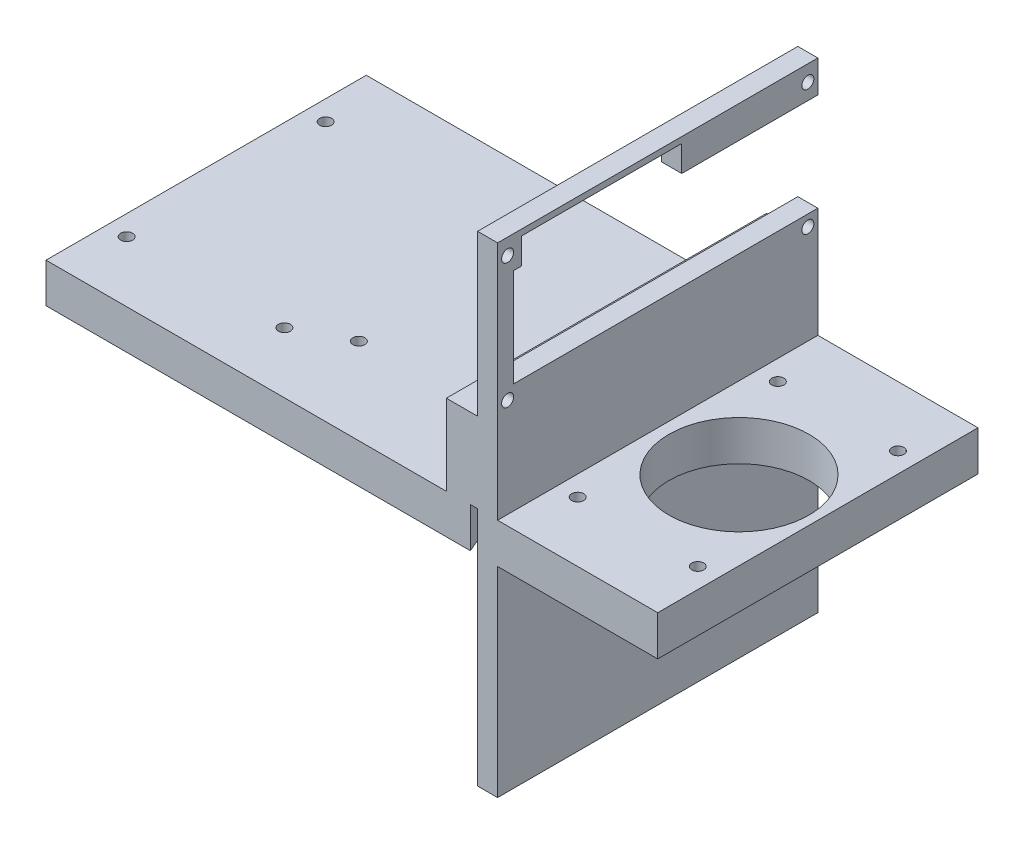
SolidWorks part; units mm, degrees
ref_plane "Front Plane" through (0, 0, 0) normal (0, 0, 1) x (1, 0, 0)
ref_plane "Top Plane" through (0, 0, 0) normal (0, 1, 0) x (1, 0, 0)
ref_plane "Right Plane" through (0, 0, 0) normal (1, 0, 0) x (0, 0, -1)
sketch "Sketch1" plane through (0, 0, 0) normal (0, 0, 1) x (1, 0, 0)
  line L0 (0, 0) -> (0, 30)
  line L1 (0, 30) -> (12.8, 30)
  line L2 (12.8, 30) -> (12.8, 0)
  line L3 (12.8, 0) -> (7.8, 0)
  line L4 (7.8, 0) -> (7.8, 10)
  line L5 (7.8, 10) -> (6, 10)
  line L6 (6, 10) -> (6, 0)
  line L7 (6, 0) -> (0, 0)
  dimension "D1" = 1.8
  dimension "D2" = 6
  dimension "D3" = 5
  dimension "D4" = 30
  dimension "D5" = 10
extrude "Boss-Extrude1" add sketch "Sketch1" along normal blind 80
sketch "Sketch3" plane through (0, 0, 0) normal (0, -1, 0) x (1, 0, 0)
  line L0 (7.8, 80) -> (12.8, 80)
  line L1 (12.8, 80) -> (12.8, 0)
  line L2 (12.8, 0) -> (7.8, 0)
  line L3 (7.8, 0) -> (7.8, 80)
sketch "Esboço2" plane through (0, 0, 0) normal (0, -1, 0) x (1, 0, 0)
  line L0 (6, 80) -> (6, 0)
  arc A0 (6, 80) -> (6, 0) centre (93.9293, 40) ccw
  dimension "D1" = 96.6
extrude "Corte-extrusão1" cut sketch "Esboço2" against normal blind 10
extrude "Boss-Extrude2" add sketch "Sketch3" along normal blind 50
sketch "Sketch4" plane through (0, 0, 0) normal (-1, 0, 0) x (0, 0, 1)
  line L0 (80, 30) -> (80, 0) construction
  line L1 (80, 9.8625) -> (0, 9.8625)
  line L2 (80, 9.8625) -> (80, 0)
  line L3 (80, 0) -> (0, 0)
  line L4 (0, 9.8625) -> (0, 0)
extrude "Boss-Extrude3" add sketch "Sketch4" along normal blind 100
sketch "Sketch5" plane through (0, 9.8625, 0) normal (0, 1, 0) x (1, 0, 0)
  line L0 (-100, -80) -> (0, -80) construction
  line L2 (-100, 0) -> (0, 0) construction
  line L3 (-100, -80) -> (-100, 0) construction
  circle A5 centre (-6.5, -21.55) radius 1.5
  circle A6 centre (-6.5, -58.45) radius 1.5
  circle A7 centre (-43.4, -21.55) radius 1.5
  circle A8 centre (-43.4, -58.45) radius 1.5
  circle A9 centre (-55.6, -64.85) radius 1.5
  circle A10 centre (-95, -64.85) radius 1.5
  circle A11 centre (-95, -15.15) radius 1.5
  point P26 (0, 0)
  point P31 (0, 0)
  point P32 (0, 0)
  dimension "D9" = 3
  dimension "D14" = 3
  dimension "D2" = 12.2
  dimension "D10" = 36.9
  dimension "D11" = 36.9
  dimension "D12" = 21.55
  dimension "D15" = 39.4
  dimension "D16" = 49.7
  dimension "D17" = 5
  dimension "D18" = 15.15
extrude "Cut-Extrude1" cut sketch "Sketch5" against normal blind 40
sketch "Sketch6" plane through (0, 30, 0) normal (0, 1, 0) x (1, 0, 0)
  line L0 (12.8, -80) -> (0, -80) construction
  line L1 (12.8, 0) -> (7.8, 0)
  line L2 (12.8, 0) -> (12.8, -80)
  line L3 (12.8, -80) -> (7.8, -80)
  line L4 (7.8, 0) -> (7.8, -80)
  dimension "D1" = 5
extrude "Boss-Extrude4" add sketch "Sketch6" along normal blind 40
sketch "Sketch7" plane through (12.8, 0, 0) normal (1, 0, 0) x (0, 0, -1)
  line L0 (-74, 68.5) -> (-74, 62)
  line L1 (-74, 62) -> (-76, 62)
  line L2 (-76, 62) -> (-76, 37.5)
  line L3 (-76, 37.5) -> (0, 37.5)
  line L4 (0, 37.5) -> (0, 62)
  line L5 (0, 62) -> (-34, 62)
  line L6 (-34, 62) -> (-34, 68.5)
  line L7 (-34, 68.5) -> (-74, 68.5)
  line L8 (-80, -50) -> (-80, 70) construction
  line L9 (-80, 70) -> (0, 70) construction
  line L10 (-85.9777, 68.5) -> (4.9186, 68.5) construction
  line L11 (-85.9777, 32.2) -> (4.9186, 32.2) construction
  line L12 (0, -50) -> (0, 70) construction
  circle A0 centre (-77.5, 66) radius 1.5
  circle A1 centre (-2.5, 66) radius 1.5
  circle A2 centre (-2.5, 34.7) radius 1.5
  circle A3 centre (-77.5, 34.7) radius 1.5
  point P24 (0, 0)
  point P25 (0, 0)
  point P26 (0, 0)
  point P27 (0, 0)
  dimension "D9" = 3
  dimension "D1" = 76
  dimension "D2" = 4
  dimension "D3" = 6.5
  dimension "D4" = 24.5
  dimension "D5" = 8
  dimension "D6" = 40
  dimension "D7" = 2
  dimension "D8" = 5.3
  dimension "D10" = 2.5
  dimension "D11" = 2.5
  dimension "D12" = 2.5
  dimension "D13" = 2.5
extrude "Cut-Extrude2" cut sketch "Sketch7" against normal blind 40
sketch "Sketch8" plane through (12.8, 0, 0) normal (1, 0, 0) x (0, 0, -1)
  line L0 (-80, -50) -> (-80, 70) construction
  line L1 (-80, 10) -> (0, 10)
  line L2 (-80, 10) -> (-80, 0)
  line L3 (-80, 0) -> (0, 0)
  line L4 (0, 10) -> (0, 0)
extrude "Boss-Extrude5" add sketch "Sketch8" along normal blind 40
sketch "Sketch9" plane through (0, 10, 0) normal (0, 1, 0) x (1, 0, 0)
  line L0 (52.8, 0) -> (52.8, -80) construction
  line L2 (52.8, -80) -> (12.8, -80) construction
  circle A0 centre (47.8, -65) radius 1.5
  circle A1 centre (17.8, -65) radius 1.5
  circle A2 centre (47.8, -15) radius 1.5
  circle A3 centre (17.8, -15) radius 1.5
  circle A4 centre (33.0995, -40) radius 17.5
  dimension "D1" = 50
  dimension "D2" = 30
  dimension "D3" = 29.0018
  dimension "D4" = 29.0018
  dimension "D5" = 5
  dimension "D6" = 15
extrude "Cut-Extrude3" cut sketch "Sketch9" against normal blind 40
